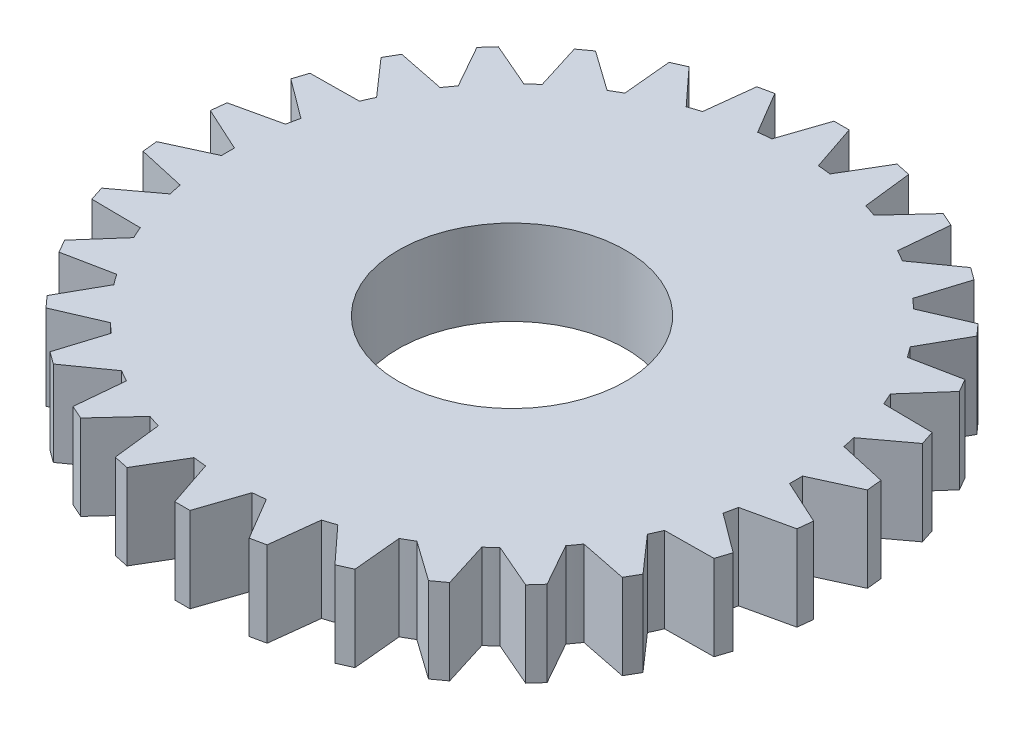
SolidWorks part; units mm, degrees
ref_plane "Front Plane" through (0, 0, 0) normal (0, 0, 1) x (1, 0, 0)
ref_plane "Top Plane" through (0, 0, 0) normal (0, 1, 0) x (1, 0, 0)
ref_plane "Right Plane" through (0, 0, 0) normal (1, 0, 0) x (0, 0, -1)
sketch "Sketch1" plane through (0, 0, 0) normal (0, 1, 0) x (1, 0, 0)
  line L4 (-0.1335, 5.8) -> (0.1335, 5.8)
  line L5 (-0.409, 4.9832) -> (-0.1335, 5.8)
  line L6 (0.409, 4.9832) -> (0.1335, 5.8)
  line L7 (1.4361, 4.7893) -> (1.3365, 5.6455)
  line L8 (1.0753, 5.701) -> (1.3365, 5.6455)
  line L9 (0.636, 4.9594) -> (1.0753, 5.701)
  line L10 (2.4005, 4.3861) -> (2.4811, 5.2442)
  line L11 (2.2371, 5.3529) -> (2.4811, 5.2442)
  line L12 (1.6532, 4.7188) -> (2.2371, 5.3529)
  line L13 (3.26, 3.7911) -> (3.5172, 4.6138)
  line L14 (3.3011, 4.7708) -> (3.5172, 4.6138)
  line L15 (2.5982, 4.2719) -> (3.3011, 4.7708)
  line L16 (3.9769, 3.0305) -> (4.3996, 3.7817)
  line L17 (4.2209, 3.9802) -> (4.3996, 3.7817)
  line L18 (3.4296, 3.6384) -> (4.2209, 3.9802)
  line L19 (4.5201, 2.1374) -> (5.0897, 2.7843)
  line L20 (4.9562, 3.0157) -> (5.0897, 2.7843)
  line L21 (4.1111, 2.8458) -> (4.9562, 3.0157)
  line L22 (4.8657, 1.1509) -> (5.5574, 1.6653)
  line L23 (5.4749, 1.9193) -> (5.5574, 1.6653)
  line L24 (4.613, 1.9289) -> (5.4749, 1.9193)
  line L25 (4.9987, 0.1141) -> (5.7822, 0.4734)
  line L26 (5.7543, 0.7391) -> (5.7822, 0.4734)
  line L27 (4.9132, 0.9276) -> (5.7543, 0.7391)
  line L28 (4.9132, -0.9276) -> (5.7543, -0.7391)
  line L29 (5.7822, -0.4734) -> (5.7543, -0.7391)
  line L30 (4.9987, -0.1141) -> (5.7822, -0.4734)
  line L31 (4.613, -1.9289) -> (5.4749, -1.9193)
  line L32 (5.5574, -1.6653) -> (5.4749, -1.9193)
  line L33 (4.8657, -1.1509) -> (5.5574, -1.6653)
  line L34 (4.1111, -2.8458) -> (4.9562, -3.0157)
  line L35 (5.0897, -2.7843) -> (4.9562, -3.0157)
  line L36 (4.5201, -2.1374) -> (5.0897, -2.7843)
  line L37 (3.4296, -3.6384) -> (4.2209, -3.9802)
  line L38 (4.3996, -3.7817) -> (4.2209, -3.9802)
  line L39 (3.9769, -3.0305) -> (4.3996, -3.7817)
  line L40 (2.5982, -4.2719) -> (3.3011, -4.7708)
  line L41 (3.5172, -4.6138) -> (3.3011, -4.7708)
  line L42 (3.26, -3.7911) -> (3.5172, -4.6138)
  line L43 (1.6532, -4.7188) -> (2.2371, -5.3529)
  line L44 (2.4811, -5.2442) -> (2.2371, -5.3529)
  line L45 (2.4005, -4.3861) -> (2.4811, -5.2442)
  line L46 (0.636, -4.9594) -> (1.0753, -5.701)
  line L47 (1.3365, -5.6455) -> (1.0753, -5.701)
  line L48 (1.4361, -4.7893) -> (1.3365, -5.6455)
  line L49 (-0.409, -4.9832) -> (-0.1335, -5.8)
  line L50 (0.1335, -5.8) -> (-0.1335, -5.8)
  line L51 (0.409, -4.9832) -> (0.1335, -5.8)
  line L52 (-1.4361, -4.7893) -> (-1.3365, -5.6455)
  line L53 (-1.0753, -5.701) -> (-1.3365, -5.6455)
  line L54 (-0.636, -4.9594) -> (-1.0753, -5.701)
  line L55 (-2.4005, -4.3861) -> (-2.4811, -5.2442)
  line L56 (-2.2371, -5.3529) -> (-2.4811, -5.2442)
  line L57 (-1.6532, -4.7188) -> (-2.2371, -5.3529)
  line L58 (-3.26, -3.7911) -> (-3.5172, -4.6138)
  line L59 (-3.3011, -4.7708) -> (-3.5172, -4.6138)
  line L60 (-2.5982, -4.2719) -> (-3.3011, -4.7708)
  line L61 (-3.9769, -3.0305) -> (-4.3996, -3.7817)
  line L62 (-4.2209, -3.9802) -> (-4.3996, -3.7817)
  line L63 (-3.4296, -3.6384) -> (-4.2209, -3.9802)
  line L64 (-4.5201, -2.1374) -> (-5.0897, -2.7843)
  line L65 (-4.9562, -3.0157) -> (-5.0897, -2.7843)
  line L66 (-4.1111, -2.8458) -> (-4.9562, -3.0157)
  line L67 (-4.8657, -1.1509) -> (-5.5574, -1.6653)
  line L68 (-5.4749, -1.9193) -> (-5.5574, -1.6653)
  line L69 (-4.613, -1.9289) -> (-5.4749, -1.9193)
  line L70 (-4.9987, -0.1141) -> (-5.7822, -0.4734)
  line L71 (-5.7543, -0.7391) -> (-5.7822, -0.4734)
  line L72 (-4.9132, -0.9276) -> (-5.7543, -0.7391)
  line L73 (-4.9132, 0.9276) -> (-5.7543, 0.7391)
  line L74 (-5.7822, 0.4734) -> (-5.7543, 0.7391)
  line L75 (-4.9987, 0.1141) -> (-5.7822, 0.4734)
  line L76 (-4.613, 1.9289) -> (-5.4749, 1.9193)
  line L77 (-5.5574, 1.6653) -> (-5.4749, 1.9193)
  line L78 (-4.8657, 1.1509) -> (-5.5574, 1.6653)
  line L79 (-4.1111, 2.8458) -> (-4.9562, 3.0157)
  line L80 (-5.0897, 2.7843) -> (-4.9562, 3.0157)
  line L81 (-4.5201, 2.1374) -> (-5.0897, 2.7843)
  line L82 (-3.4296, 3.6384) -> (-4.2209, 3.9802)
  line L83 (-4.3996, 3.7817) -> (-4.2209, 3.9802)
  line L84 (-3.9769, 3.0305) -> (-4.3996, 3.7817)
  line L85 (-2.5982, 4.2719) -> (-3.3011, 4.7708)
  line L86 (-3.5172, 4.6138) -> (-3.3011, 4.7708)
  line L87 (-3.26, 3.7911) -> (-3.5172, 4.6138)
  line L88 (-1.6532, 4.7188) -> (-2.2371, 5.3529)
  line L89 (-2.4811, 5.2442) -> (-2.2371, 5.3529)
  line L90 (-2.4005, 4.3861) -> (-2.4811, 5.2442)
  line L91 (-0.636, 4.9594) -> (-1.0753, 5.701)
  line L92 (-1.3365, 5.6455) -> (-1.0753, 5.701)
  line L93 (-1.4361, 4.7893) -> (-1.3365, 5.6455)
  arc A0 (-0.409, 4.9832) -> (-0.636, 4.9594) centre (0, 0) ccw
  arc A1 (-2.4005, 4.3861) -> (-2.5982, 4.2719) centre (0, 0) ccw
  arc A2 (-1.4361, 4.7893) -> (-1.6532, 4.7188) centre (0, 0) ccw
  arc A3 (-3.26, 3.7911) -> (-3.4296, 3.6384) centre (0, 0) ccw
  arc A4 (-3.9769, 3.0305) -> (-4.1111, 2.8458) centre (0, 0) ccw
  arc A5 (-4.5201, 2.1374) -> (-4.613, 1.9289) centre (0, 0) ccw
  arc A6 (-4.8657, 1.1509) -> (-4.9132, 0.9276) centre (0, 0) ccw
  arc A7 (-4.9987, 0.1141) -> (-4.9987, -0.1141) centre (0, 0) ccw
  arc A8 (-4.9132, -0.9276) -> (-4.8657, -1.1509) centre (0, 0) ccw
  arc A9 (-4.613, -1.9289) -> (-4.5201, -2.1374) centre (0, 0) ccw
  arc A10 (-4.1111, -2.8458) -> (-3.9769, -3.0305) centre (0, 0) ccw
  arc A11 (-3.4296, -3.6384) -> (-3.26, -3.7911) centre (0, 0) ccw
  arc A12 (-2.5982, -4.2719) -> (-2.4005, -4.3861) centre (0, 0) ccw
  arc A13 (-1.6532, -4.7188) -> (-1.4361, -4.7893) centre (0, 0) ccw
  arc A14 (-0.636, -4.9594) -> (-0.409, -4.9832) centre (0, 0) ccw
  arc A15 (0.409, -4.9832) -> (0.636, -4.9594) centre (0, 0) ccw
  arc A16 (1.4361, -4.7893) -> (1.6532, -4.7188) centre (0, 0) ccw
  arc A17 (2.4005, -4.3861) -> (2.5982, -4.2719) centre (0, 0) ccw
  arc A18 (3.26, -3.7911) -> (3.4296, -3.6384) centre (0, 0) ccw
  arc A19 (3.9769, -3.0305) -> (4.1111, -2.8458) centre (0, 0) ccw
  arc A20 (4.5201, -2.1374) -> (4.613, -1.9289) centre (0, 0) ccw
  arc A21 (4.8657, -1.1509) -> (4.9132, -0.9276) centre (0, 0) ccw
  arc A22 (0.636, 4.9594) -> (0.409, 4.9832) centre (0, 0) ccw
  arc A23 (1.4361, 4.7893) -> (0.636, 4.9594) centre (0, 0) ccw construction
  arc A24 (4.9987, -0.1141) -> (4.9987, 0.1141) centre (0, 0) ccw
  arc A25 (4.9132, -0.9276) -> (4.9987, -0.1141) centre (0, 0) ccw construction
  arc A26 (1.6532, 4.7188) -> (1.4361, 4.7893) centre (0, 0) ccw
  arc A27 (2.4005, 4.3861) -> (1.6532, 4.7188) centre (0, 0) ccw construction
  arc A28 (2.5982, 4.2719) -> (2.4005, 4.3861) centre (0, 0) ccw
  arc A29 (3.26, 3.7911) -> (2.5982, 4.2719) centre (0, 0) ccw construction
  arc A30 (3.4296, 3.6384) -> (3.26, 3.7911) centre (0, 0) ccw
  arc A31 (3.9769, 3.0305) -> (3.4296, 3.6384) centre (0, 0) ccw construction
  arc A32 (4.1111, 2.8458) -> (3.9769, 3.0305) centre (0, 0) ccw
  arc A33 (4.5201, 2.1374) -> (4.1111, 2.8458) centre (0, 0) ccw construction
  arc A34 (4.613, 1.9289) -> (4.5201, 2.1374) centre (0, 0) ccw
  arc A35 (4.8657, 1.1509) -> (4.613, 1.9289) centre (0, 0) ccw construction
  arc A36 (4.9132, 0.9276) -> (4.8657, 1.1509) centre (0, 0) ccw
  arc A37 (4.9987, 0.1141) -> (4.9132, 0.9276) centre (0, 0) ccw construction
  point P7 (0, 5)
  dimension "D1" = 10
  dimension "D2" = 0.8
  dimension "D3" = 30
extrude "Boss-Extrude1" add sketch "Sketch1" along normal blind 1.5
sketch "Sketch2" plane through (0, 1.5, 0) normal (0, 1, 0) x (1, 0, 0)
  circle A0 centre (0, 0) radius 2
extrude "Cut-Extrude1" cut sketch "Sketch2" against normal through all
